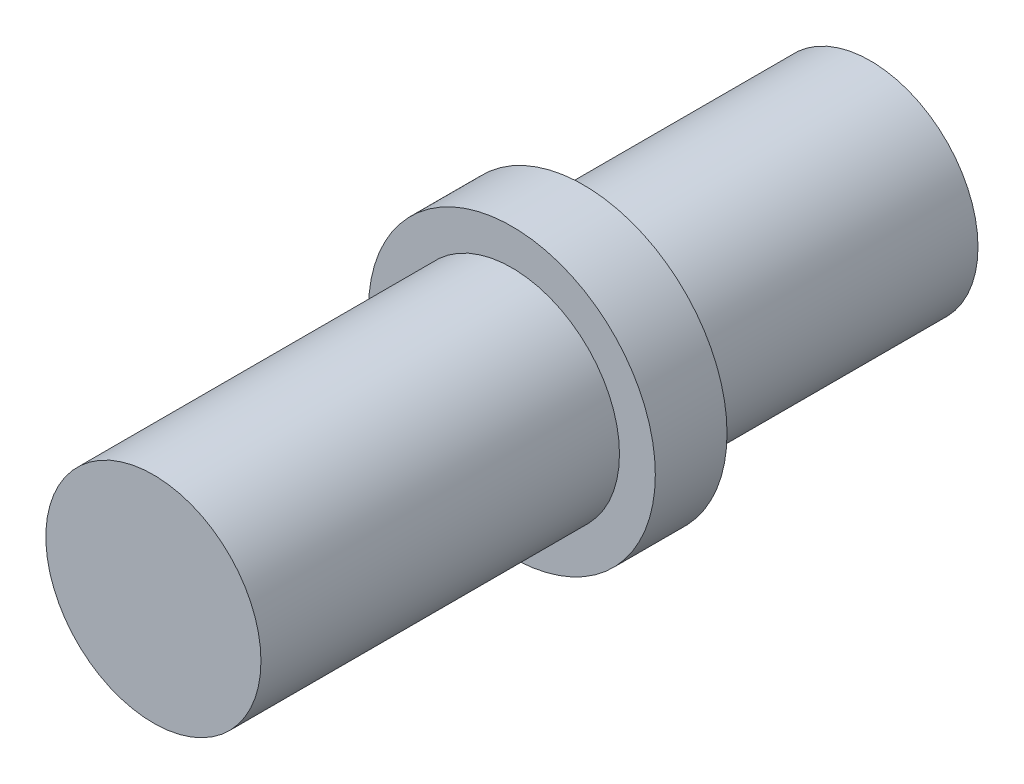
SolidWorks part; units mm, degrees
ref_plane "Front Plane" through (0, 0, 0) normal (0, 0, 1) x (1, 0, 0)
ref_plane "Top Plane" through (0, 0, 0) normal (0, 1, 0) x (1, 0, 0)
ref_plane "Right Plane" through (0, 0, 0) normal (1, 0, 0) x (0, 0, -1)
other "Configuration Table"
sketch "Sketch2" plane through (0, 0, 0) normal (0, 0, 1) x (1, 0, 0)
  circle A0 centre (0, 0) radius 3
extrude "Locator_shaft" add sketch "Sketch2" along normal blind 20 from offset 0
sketch "Sketch3" plane through (0, 0, 0) normal (0, 0, 1) x (1, 0, 0)
  circle A0 centre (0, 0) radius 4
extrude "Locator_shoulder" add sketch "Sketch3" along normal blind 2 from offset 8
